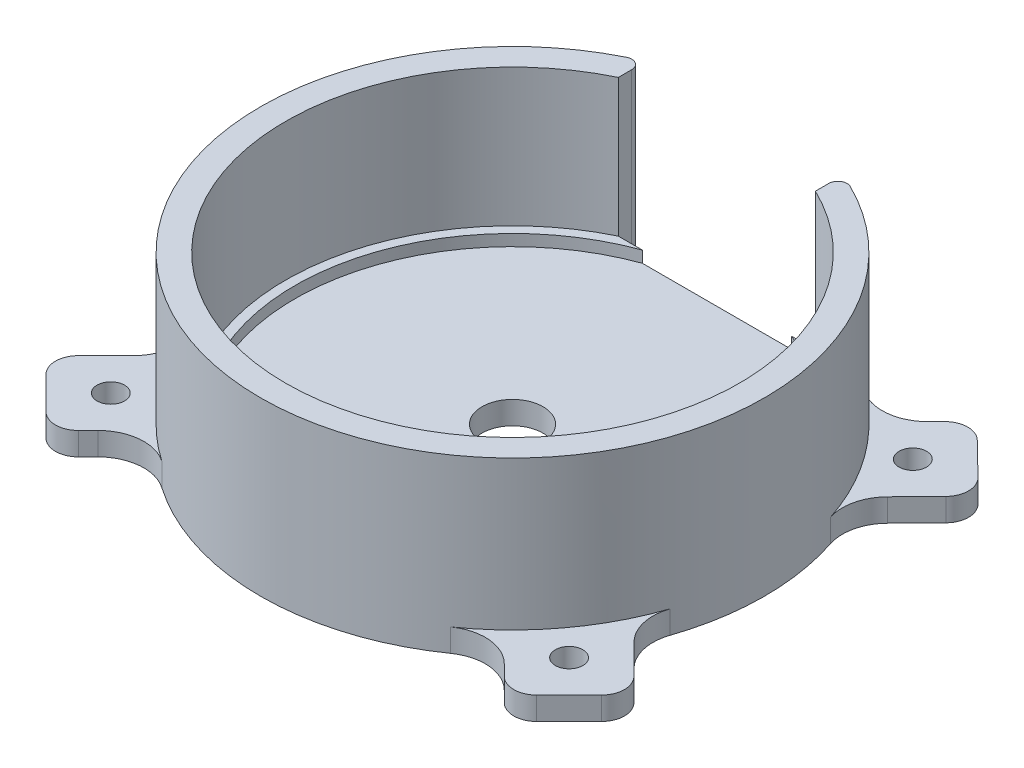
SolidWorks part; units mm, degrees
ref_plane "前视基准面" through (0, 0, 0) normal (0, 0, 1) x (1, 0, 0)
ref_plane "上视基准面" through (0, 0, 0) normal (0, 1, 0) x (1, 0, 0)
ref_plane "右视基准面" through (0, 0, 0) normal (1, 0, 0) x (0, 0, -1)
other "Configuration Table"
sketch "草图1" plane through (0, 0, 0) normal (0, 1, 0) x (1, 0, 0)
  circle A0 centre (0, 0) radius 55
  dimension "D1" = 110
extrude "凸台-拉伸1" add sketch "草图1" along normal blind 37.5
sketch "草图3" plane through (0, 37.5, 0) normal (0, 1, 0) x (1, 0, 0)
  circle A0 centre (0, 0) radius 49.5
  dimension "D1" = 99
extrude "切除-拉伸1" cut sketch "草图3" against normal blind 32.5
sketch "草图5" plane through (0, 37.5, 0) normal (0, 1, 0) x (1, 0, 0)
  line L0 (0, 0) -> (0, 49.5) construction
  line L1 (-21.5, 44.587) -> (21.5, 44.587)
  line L2 (-21.5, 44.587) -> (-21.5, 56.8299)
  line L3 (-21.5, 56.8299) -> (21.5, 56.8299)
  line L4 (21.5, 56.8299) -> (21.5, 44.587)
  circle A0 centre (0, 0) radius 49.5 construction
  circle A1 centre (0, 0) radius 49.5 construction
  dimension "D1" = 43
extrude "切除-拉伸2" cut sketch "草图5" against normal blind 40
fillet "圆角4" radius 2 1 edges at (-21.5, 18.75, -50.6236)
fillet "圆角5" radius 2 1 edges at (21.5, 18.75, -50.6236)
sketch "草图6" plane through (0, 5, 0) normal (0, 1, 0) x (1, 0, 0)
  circle A0 centre (0, 0) radius 6.65
  dimension "D1" = 13.3
extrude "切除-拉伸3" cut sketch "草图6" against normal blind 12 contours A0
sketch "草图10" plane through (0, 5, 0) normal (0, 1, 0) x (1, 0, 0)
  line L0 (-49.7204, 37.0712) -> (62.5452, 37.0712) construction
  line L1 (-49.7204, 37.0712) -> (-49.7204, -35.3765) construction
  line L2 (-49.7204, -37.9288) -> (73.1761, -37.9288) construction
  circle A0 centre (-49.7204, 37.0712) radius 3
  circle A1 centre (50.2796, 37.0712) radius 3
  circle A2 centre (-49.7204, -37.9288) radius 3
  circle A3 centre (50.2796, -37.9288) radius 3
  dimension "D1" = 6
  dimension "D2" = 6
  dimension "D4" = 6
  dimension "D6" = 6
  dimension "D3" = 100
  dimension "D5" = 75
  dimension "D7" = 100
sketch "草图14" plane through (0, 5, 0) normal (0, 1, 0) x (1, 0, 0)
  line L0 (-49.8986, 23.1329) -> (-63.8625, 37.0448)
  line L1 (-63.8625, 37.0448) -> (-49.7468, 51.2133)
  line L2 (-49.7468, 51.2133) -> (-38.1286, 39.6385)
  line L3 (49.8119, -23.319) -> (64.4217, -37.9288)
  line L4 (-49.6324, -23.6986) -> (-63.8626, -37.9288)
  line L5 (-63.8626, -37.9288) -> (-49.7204, -52.0709)
  line L6 (-49.7204, -52.0709) -> (-37.6979, -40.0484)
  line L7 (38.4757, 39.3016) -> (50.1189, 51.2124)
  line L8 (50.1189, 51.2124) -> (64.4208, 37.2319)
  line L9 (64.4208, 37.2319) -> (50.1345, 22.6171)
  line L10 (64.4217, -37.9288) -> (50.2796, -52.0709)
  line L11 (50.2796, -52.0709) -> (37.9849, -39.7762)
  arc A0 (-24.3868, 49.2979) -> (24.3868, 49.2979) centre (0, 0) ccw construction
  arc A1 (-49.6324, -23.6986) -> (-37.6979, -40.0484) centre (0, 0) ccw
  arc A2 (-49.8986, 23.1329) -> (-38.1286, 39.6385) centre (0, 0) cw
  arc A3 (38.4757, 39.3016) -> (50.1345, 22.6171) centre (0, 0) cw
  arc A4 (49.8119, -23.319) -> (37.9849, -39.7762) centre (0, 0) cw
  dimension "D1" = 10
  dimension "D2" = 10
  dimension "D3" = 10
  dimension "D4" = 10
  dimension "D5" = 10
  dimension "D6" = 10
  dimension "D7" = 10
  dimension "D8" = 10
  dimension "D9" = 10
  dimension "D10" = 10
  dimension "D11" = 10
  dimension "D12" = 10
extrude "凸台-拉伸3" add sketch "草图14" against normal up to surface (5 mm away) up to face at (0, 0, 6.65)
fillet "圆角7" radius 10 8 edges at (-49.6324, 2.5, 23.6986) (-37.6979, 2.5, 40.0484) (37.9849, 2.5, 39.7762) (49.8119, 2.5, 23.319) (50.1345, 2.5, -22.6171) (38.4757, 2.5, -39.3016) (-38.1286, 2.5, -39.6385) (-49.8986, 2.5, -23.1329)
fillet "圆角8" radius 5 8 edges at (-49.7468, 2.5, -51.2133) (-63.8625, 2.5, -37.0448) (-63.8626, 2.5, 37.9288) (-49.7204, 2.5, 52.0709) (50.2796, 2.5, 52.0709) (64.4217, 2.5, 37.9288) (64.4208, 2.5, -37.2319) (50.1189, 2.5, -51.2124)
extrude "切除-拉伸5" cut sketch "草图10" against normal up to surface (5 mm away) up to face at (0, 0, 6.65)
sketch "草图15" plane through (0, 5, 0) normal (0, 1, 0) x (1, 0, 0)
  line L0 (-21.5, 44.587) -> (21.5, 44.587) construction
  line L1 (-21.5, 44.587) -> (-16.2558, 44.587)
  line L2 (16.2558, 44.587) -> (21.5, 44.587)
  arc A0 (-21.5, 44.587) -> (21.5, 44.587) centre (0, 0) ccw
  arc A1 (-16.2558, 44.587) -> (16.2558, 44.587) centre (0, 0) ccw
extrude "凸台-拉伸4" add sketch "草图15" along normal blind 2.5
